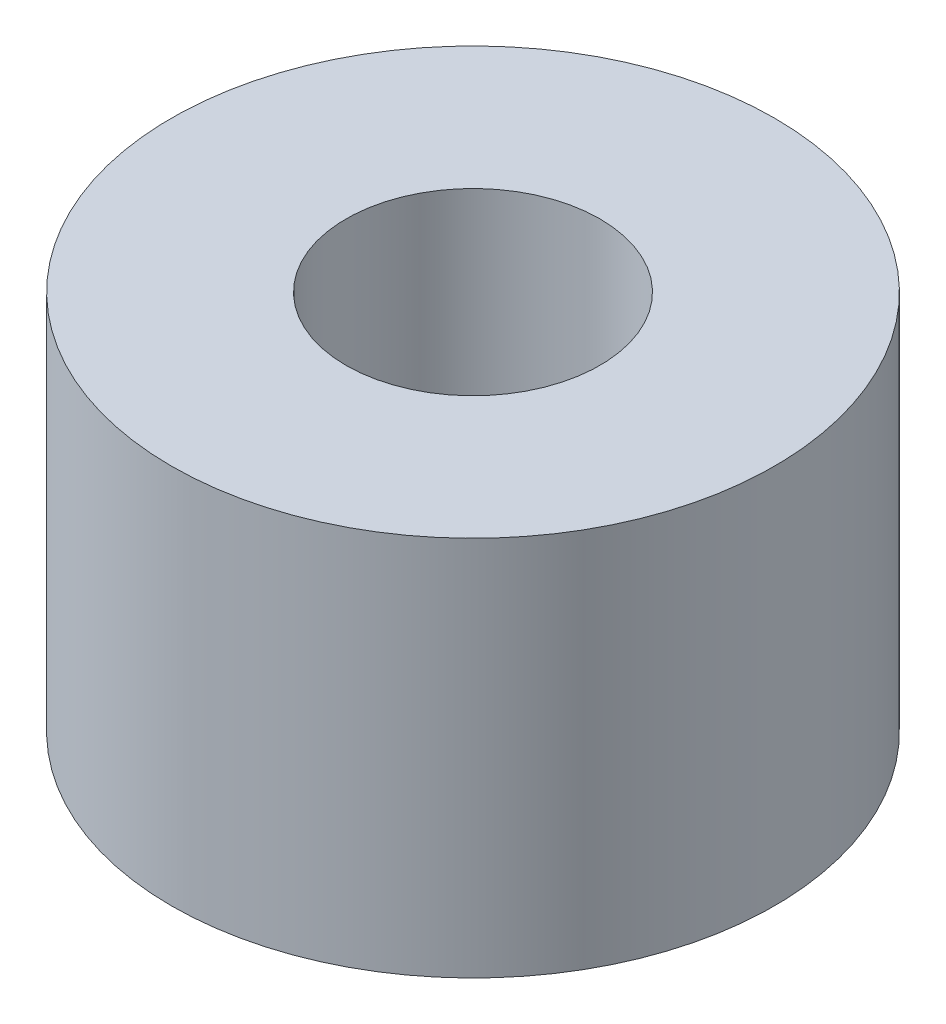
SolidWorks part; units mm, degrees
ref_plane "Alzado" through (0, 0, 0) normal (0, 0, 1) x (1, 0, 0)
ref_plane "Planta" through (0, 0, 0) normal (0, 1, 0) x (1, 0, 0)
ref_plane "Vista lateral" through (0, 0, 0) normal (1, 0, 0) x (0, 0, -1)
sketch "Croquis1" plane through (0, 0, 0) normal (0, 1, 0) x (1, 0, 0)
  circle A0 centre (0, 0) radius 4
  circle A1 centre (0, 0) radius 9.5
  dimension "D1" = 19
  dimension "D2" = 8
extrude "Saliente-Extruir1" add sketch "Croquis1" along normal blind 12
